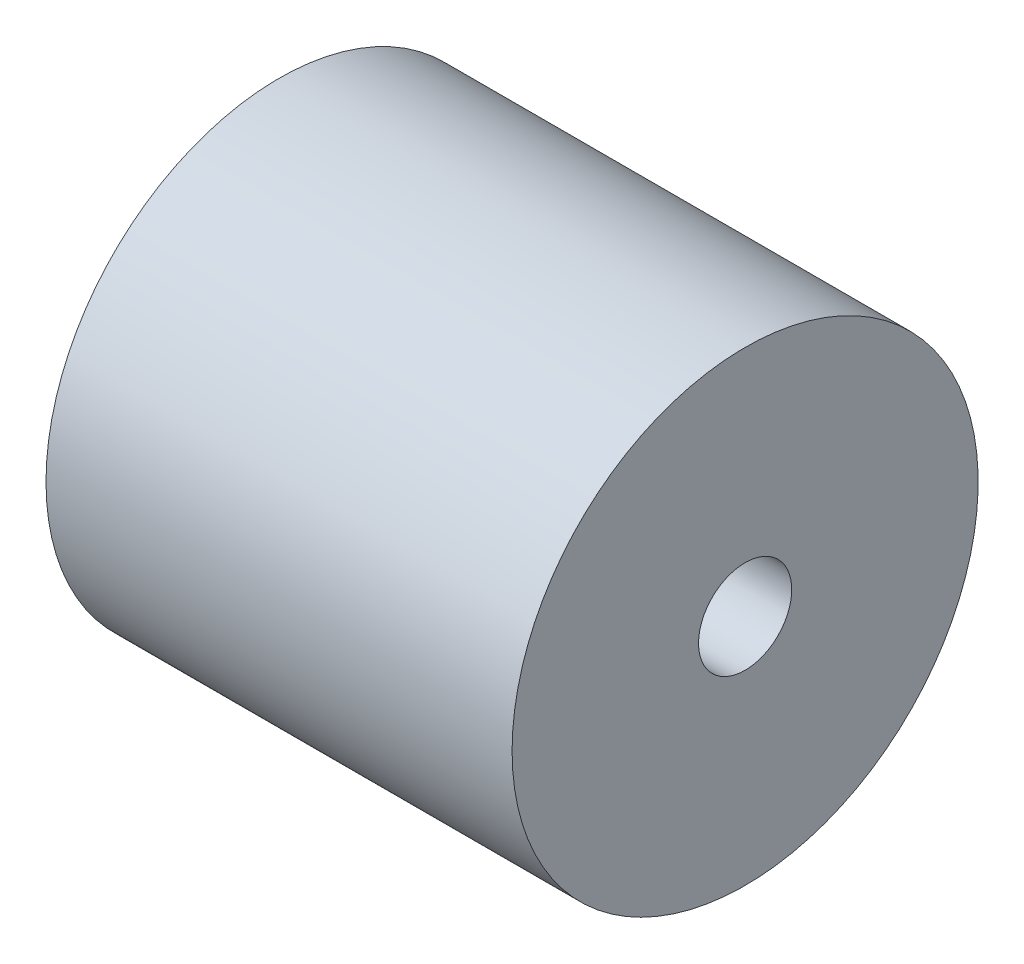
SolidWorks part; units mm, degrees
ref_plane "Front Plane" through (0, 0, 0) normal (0, 0, 1) x (1, 0, 0)
ref_plane "Top Plane" through (0, 0, 0) normal (0, 1, 0) x (1, 0, 0)
ref_plane "Right Plane" through (0, 0, 0) normal (1, 0, 0) x (0, 0, -1)
sketch "Sketch1" plane through (0, 0, 0) normal (0, 0, 1) x (1, 0, 0)
  line L0 (63.5, 0) -> (199.6587, 0) construction
  line L2 (0, 6.35) -> (0, 31.75)
  line L3 (0, 31.75) -> (63.5, 31.75)
  line L4 (63.5, 6.35) -> (63.5, 31.75)
  line L5 (63.5, 6.35) -> (0, 6.35)
  dimension "D1" = 63.5
  dimension "D2" = 63.5
  dimension "D3" = 12.7
revolve "Revolve1" add sketch "Sketch1" angle 360 about L0
